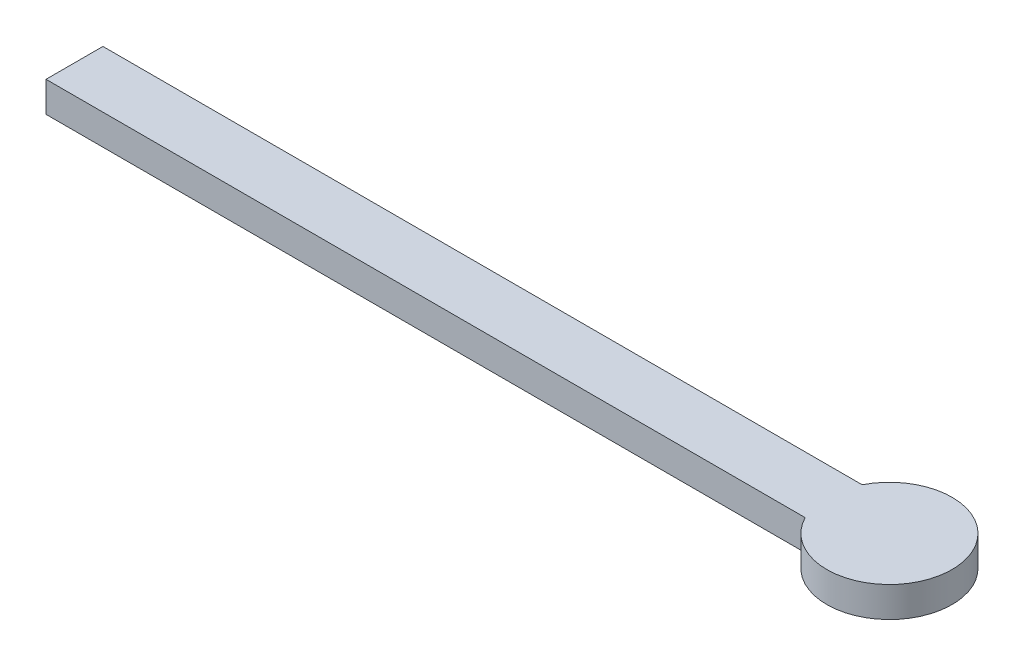
SolidWorks part; units mm, degrees
ref_plane "Front Plane" through (0, 0, 0) normal (0, 0, 1) x (1, 0, 0)
ref_plane "Top Plane" through (0, 0, 0) normal (0, 1, 0) x (1, 0, 0)
ref_plane "Right Plane" through (0, 0, 0) normal (1, 0, 0) x (0, 0, -1)
sketch "Sketch1" plane through (0, 0, 0) normal (0, 1, 0) x (1, 0, 0)
  line L1 (-14.6969, 7.5) -> (-214.6969, 7.5)
  line L3 (-14.6969, -7.5) -> (-214.6969, -7.5)
  line L4 (-214.6969, 7.5) -> (-214.6969, -7.5)
  arc A1 (-14.6969, -7.5) -> (-14.6969, 7.5) centre (0, 0) ccw
  dimension "D1" = 16.5
  dimension "D2" = 200
  dimension "D3" = 15
extrude "Boss-Extrude1" add sketch "Sketch1" along normal blind 8
